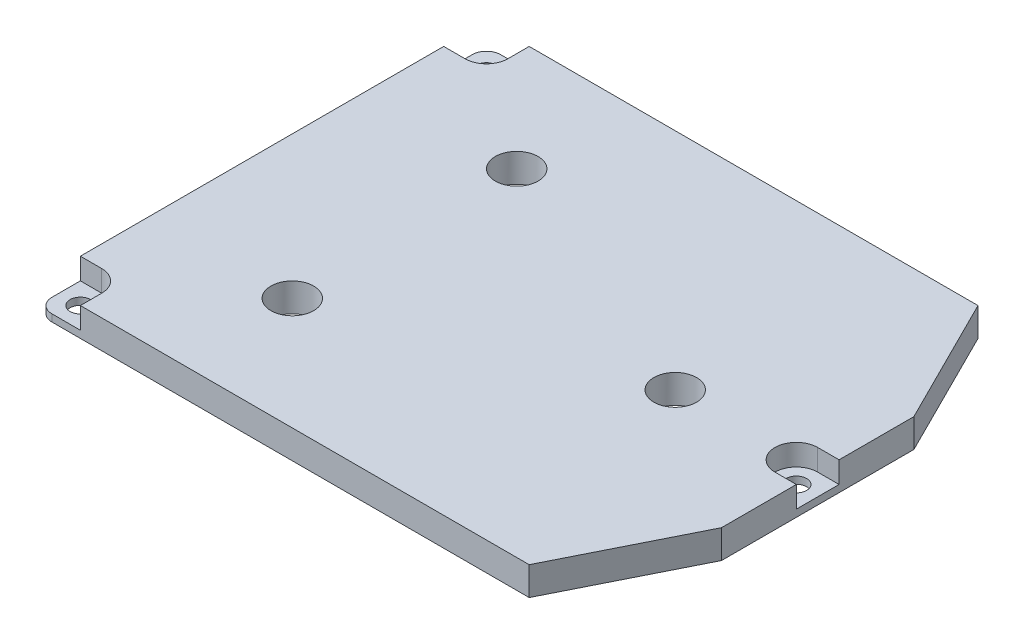
SolidWorks part; units mm, degrees
ref_plane "Alzado" through (0, 0, 0) normal (0, 0, 1) x (1, 0, 0)
ref_plane "Planta" through (0, 0, 0) normal (0, 1, 0) x (1, 0, 0)
ref_plane "Vista lateral" through (0, 0, 0) normal (1, 0, 0) x (0, 0, -1)
sketch "Croquis1" plane through (0, 0, 0) normal (0, 1, 0) x (1, 0, 0)
  line L0 (63, 0) -> (69, 0)
  line L1 (0, 0) -> (63, 0)
  line L2 (0, 0) -> (0, 63)
  line L3 (0, 63) -> (63, 63)
  line L5 (69, 0) -> (78, 18)
  line L6 (78, 18) -> (78, 45)
  line L7 (78, 45) -> (69, 63)
  line L8 (69, 63) -> (63, 63)
  dimension "D1" = 63
  dimension "D2" = 63
  dimension "D3" = 63
  dimension "D4" = 6
  dimension "D5" = 6
  dimension "D6" = 15
  dimension "D7" = 27
  dimension "D8" = 18
extrude "Saliente-Extruir1" add sketch "Croquis1" along normal blind 4
sketch "Croquis2" plane through (0, 4, 0) normal (0, 1, 0) x (1, 0, 0)
  line L0 (69, 63) -> (0, 63) construction
  line L1 (0, 63) -> (0, 0) construction
  line L2 (0, 0) -> (69, 0) construction
  line L3 (78, 18) -> (78, 45) construction
  circle A0 centre (3, 3) radius 1.45
  circle A1 centre (3, 60) radius 1.45
  circle A4 centre (75, 31.5) radius 1.45
  dimension "D1" = 2.9
  dimension "D2" = 2.9
  dimension "D13" = 2.9
  dimension "D5" = 3
  dimension "D6" = 3
  dimension "D7" = 3
  dimension "D8" = 3
  dimension "D14" = 31.5
  dimension "D15" = 3
extrude "Cortar-Extruir1" cut sketch "Croquis2" against normal blind 4
fillet "Redondeo1" radius 2 2 edges at (0, 2, -63) (0, 2, 0)
sketch "Croquis3" plane through (0, 4, 0) normal (0, 1, 0) x (1, 0, 0)
  line L1 (2, 0) -> (69, 0) construction
  line L4 (6, 3) -> (6, 0)
  line L5 (6, 0) -> (0, 0)
  line L6 (0, 0) -> (0, 3)
  line L8 (0, 3) -> (0, 6)
  line L9 (0, 6) -> (3, 6)
  line L11 (69, 63) -> (2, 63) construction
  line L13 (3, 57) -> (0, 57)
  line L14 (0, 61) -> (0, 2) construction
  line L15 (0, 57) -> (0, 63)
  line L16 (0, 63) -> (6, 63)
  line L17 (6, 63) -> (6, 60)
  line L18 (75, 28.5) -> (78, 28.5)
  line L19 (78, 18) -> (78, 45) construction
  line L20 (78, 28.5) -> (78, 34.5)
  line L21 (78, 34.5) -> (75, 34.5)
  arc A1 (6, 3) -> (3, 6) centre (3, 3) ccw
  arc A2 (3, 57) -> (6, 60) centre (3, 60) ccw
  arc A4 (75, 34.5) -> (75, 28.5) centre (75, 31.5) ccw
  dimension "D2" = 6
  dimension "D3" = 6
extrude "Cortar-Extruir2" cut sketch "Croquis3" against normal blind 3
sketch "Croquis4" plane through (0, 4, 0) normal (0, 1, 0) x (1, 0, 0)
  line L0 (69, 63) -> (6, 63) construction
  line L3 (78, 28.5) -> (78, 34.5) construction
  line L4 (6, 0) -> (69, 0) construction
  line L5 (0, 57) -> (0, 6) construction
  circle A0 centre (20, 47.25) radius 3
  circle A1 centre (20, 15.75) radius 3
  circle A2 centre (58, 31.5) radius 3
  dimension "D1" = 6
  dimension "D2" = 6
  dimension "D3" = 6
  dimension "D4" = 31.5
  dimension "D5" = 20
  dimension "D6" = 15.75
  dimension "D7" = 15.75
  dimension "D8" = 20
  dimension "D9" = 20
extrude "Cortar-Extruir3" cut sketch "Croquis4" against normal blind 10
